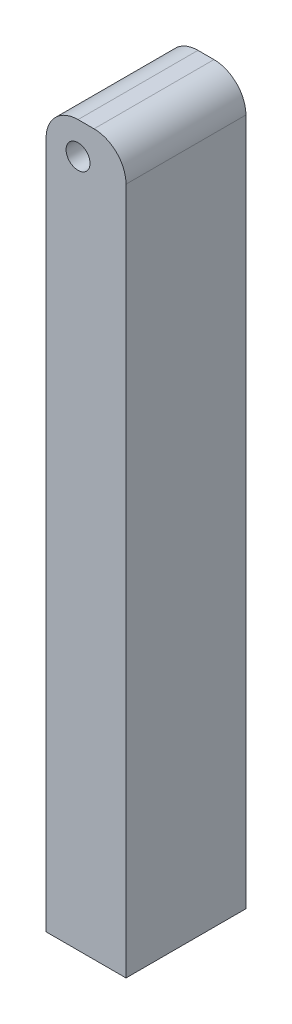
SolidWorks part; units mm, degrees
ref_plane "前视基准面" through (0, 0, 0) normal (0, 0, 1) x (1, 0, 0)
ref_plane "上视基准面" through (0, 0, 0) normal (0, 1, 0) x (1, 0, 0)
ref_plane "右视基准面" through (0, 0, 0) normal (1, 0, 0) x (0, 0, -1)
sketch "草图1" plane through (0, 0, 0) normal (0, 0, 1) x (1, 0, 0)
  line L1 (8, 0) -> (12, 0)
  line L2 (0, -8) -> (0, -180)
  line L3 (0, -180) -> (20, -180)
  line L4 (20, -8) -> (20, -180)
  arc A0 (8, 0) -> (0, -8) centre (8, -8) ccw
  arc A1 (12, 0) -> (20, -8) centre (12, -8) cw
  circle A2 centre (8, -8) radius 3
  point P7 (0, 0)
  point P10 (20, 0)
  point P12 (8, 0)
  dimension "D3" = 8
  dimension "D4" = 6
  dimension "D1" = 20
  dimension "D2" = 180
extrude "凸台-拉伸1" add sketch "草图1" along normal mid plane 30
sketch "草图2" plane through (0, -180, 0) normal (0, -1, 0) x (1, 0, 0)
  line L0 (10, 15) -> (10, -15) construction
  line L1 (0, 15) -> (20, 15) construction
  line L2 (0, -15) -> (20, -15) construction
  line L3 (20, 0) -> (0, 0) construction
  line L4 (20, 15) -> (20, -15) construction
  circle A0 centre (10, 0) radius 5
  dimension "D1" = 10
extrude "切除-拉伸1" cut sketch "草图2" against normal blind 30
